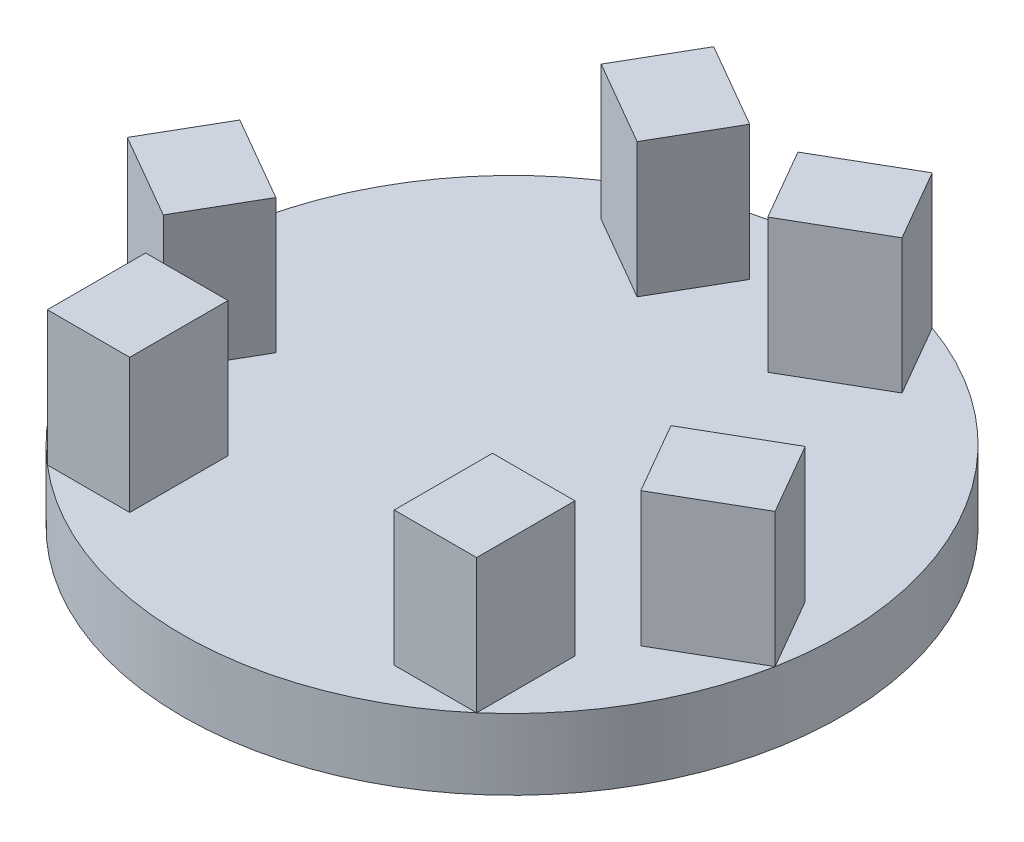
SolidWorks part; units mm, degrees
ref_plane "Plan de face" through (0, 0, 0) normal (0, 0, 1) x (1, 0, 0)
ref_plane "Plan de dessus" through (0, 0, 0) normal (0, 1, 0) x (1, 0, 0)
ref_plane "Plan de droite" through (0, 0, 0) normal (1, 0, 0) x (0, 0, -1)
sketch "Esquisse1" plane through (0, 0, 0) normal (0, 1, 0) x (1, 0, 0)
  circle A0 centre (0, 0) radius 114
  dimension "D1" = 228
extrude "Boss.-Extru.1" add sketch "Esquisse1" along normal blind 24.5
sketch "Esquisse2" plane through (0, 24.5, 0) normal (0, 1, 0) x (1, 0, 0)
  line L0 (0, 0) -> (0, -85.9808) construction
  line L1 (-8.3448, 90.5544) -> (-37.7896, 107.5544)
  line L2 (-74.25, -52.504) -> (-45.75, -52.504)
  line L3 (-74.25, -52.504) -> (-74.25, -86.504)
  line L4 (-74.25, -86.504) -> (-45.75, -86.504)
  line L5 (-45.75, -52.504) -> (-45.75, -86.504)
  line L6 (45.75, -52.504) -> (74.25, -52.504)
  line L7 (45.75, -52.504) -> (45.75, -86.504)
  line L8 (45.75, -86.504) -> (74.25, -86.504)
  line L9 (74.25, -52.504) -> (74.25, -86.504)
  line L10 (-8.3448, 90.5544) -> (-22.5948, 65.8726)
  line L11 (-22.5948, 65.8726) -> (-52.0396, 82.8726)
  line L12 (-37.7896, 107.5544) -> (-52.0396, 82.8726)
  line L13 (-68.3448, -13.3687) -> (-97.7896, 3.6313)
  line L14 (-68.3448, -13.3687) -> (-82.5948, -38.0504)
  line L15 (-82.5948, -38.0504) -> (-112.0396, -21.0504)
  line L16 (-97.7896, 3.6313) -> (-112.0396, -21.0504)
  line L17 (82.5948, -38.0504) -> (112.0396, -21.0504)
  line L18 (82.5948, -38.0504) -> (68.3448, -13.3687)
  line L19 (68.3448, -13.3687) -> (97.7896, 3.6313)
  line L20 (112.0396, -21.0504) -> (97.7896, 3.6313)
  line L21 (22.5948, 65.8726) -> (52.0396, 82.8726)
  line L22 (22.5948, 65.8726) -> (8.3448, 90.5544)
  line L23 (8.3448, 90.5544) -> (37.7896, 107.5544)
  line L24 (52.0396, 82.8726) -> (37.7896, 107.5544)
  circle A0 centre (0, 0) radius 85.9808 construction
  circle A1 centre (0, 0) radius 114 construction
  point P12 (-78.0967, 23.7987)
  point P16 (0, 0)
  point P33 (0, 0)
  dimension "D1" = 171.9615
  dimension "D2" = 34
  dimension "D3" = 28.5
  dimension "D4" = 91.5
  dimension "D5" = 3
extrude "Boss.-Extru.2" add sketch "Esquisse2" along normal blind 46.5
